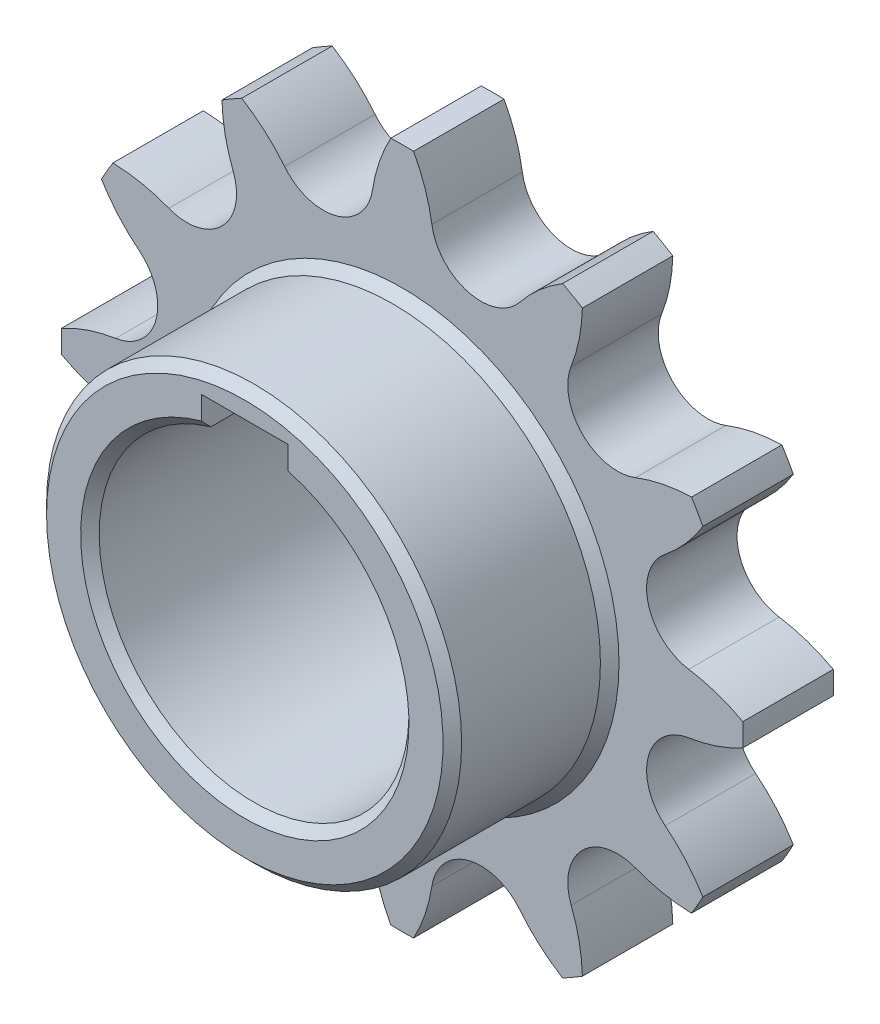
SolidWorks part; units mm, degrees
ref_plane "Front" through (0, 0, 0) normal (0, 0, 1) x (1, 0, 0)
ref_plane "Top" through (0, 0, 0) normal (0, 1, 0) x (1, 0, 0)
ref_plane "Right" through (0, 0, 0) normal (1, 0, 0) x (0, 0, -1)
sketch "Sketch1" plane through (0, 0, 0) normal (0, 0, 1) x (1, 0, 0)
  line L4 (0, -58.017) -> (0, 58.017) construction
  line L5 (-58.017, 0) -> (58.017, 0) construction
  line L6 (-1.75, -1.75) -> (1.75, 1.75)
  line L7 (-1.75, 1.75) -> (1.75, -1.75)
  circle A64 centre (0, 0) radius 41.129 construction
  circle A65 centre (0, 0) radius 49.069 construction
  arc A66 (42.4542, 18.9748) -> (46.2538, 4.7945) centre (47.4737, 12.7206) ccw
  arc A67 (54.9863, 1.8387) -> (46.2538, 4.7945) centre (42.1954, -21.5734) ccw
  arc A68 (48.5389, 25.9008) -> (46.7002, 29.0856) centre (0, 0) ccw
  arc A69 (42.4542, 18.9748) -> (48.5389, 25.9008) centre (25.7556, 39.7808) ccw
  arc A70 (27.279, 37.6597) -> (37.6597, 27.279) centre (34.7532, 34.7532) ccw
  arc A71 (46.7002, 29.0856) -> (37.6597, 27.279) centre (47.329, 2.4146) ccw
  arc A72 (29.0856, 46.7002) -> (25.9008, 48.5389) centre (0, 0) ccw
  arc A73 (27.279, 37.6597) -> (29.0856, 46.7002) centre (2.4146, 47.329) ccw
  arc A74 (4.7945, 46.2538) -> (18.9748, 42.4542) centre (12.7206, 47.4737) ccw
  arc A75 (25.9008, 48.5389) -> (18.9748, 42.4542) centre (39.7808, 25.7556) ccw
  arc A76 (1.8387, 54.9863) -> (-1.8387, 54.9863) centre (0, 0) ccw
  arc A77 (4.7945, 46.2538) -> (1.8387, 54.9863) centre (-21.5734, 42.1954) ccw
  arc A78 (-18.9748, 42.4542) -> (-4.7945, 46.2538) centre (-12.7206, 47.4737) ccw
  arc A79 (-1.8387, 54.9863) -> (-4.7945, 46.2538) centre (21.5734, 42.1954) ccw
  arc A80 (-25.9008, 48.5389) -> (-29.0856, 46.7002) centre (0, 0) ccw
  arc A81 (-18.9748, 42.4542) -> (-25.9008, 48.5389) centre (-39.7808, 25.7556) ccw
  arc A82 (-37.6597, 27.279) -> (-27.279, 37.6597) centre (-34.7532, 34.7532) ccw
  arc A83 (-29.0856, 46.7002) -> (-27.279, 37.6597) centre (-2.4146, 47.329) ccw
  arc A84 (-46.7002, 29.0856) -> (-48.5389, 25.9008) centre (0, 0) ccw
  arc A85 (-37.6597, 27.279) -> (-46.7002, 29.0856) centre (-47.329, 2.4146) ccw
  arc A86 (-46.2538, 4.7945) -> (-42.4542, 18.9748) centre (-47.4737, 12.7206) ccw
  arc A87 (-48.5389, 25.9008) -> (-42.4542, 18.9748) centre (-25.7556, 39.7808) ccw
  arc A88 (-54.9863, 1.8387) -> (-54.9863, -1.8387) centre (0, 0) ccw
  arc A89 (-46.2538, 4.7945) -> (-54.9863, 1.8387) centre (-42.1954, -21.5734) ccw
  arc A90 (-42.4542, -18.9748) -> (-46.2538, -4.7945) centre (-47.4737, -12.7206) ccw
  arc A91 (-54.9863, -1.8387) -> (-46.2538, -4.7945) centre (-42.1954, 21.5734) ccw
  arc A92 (-48.5389, -25.9008) -> (-46.7002, -29.0856) centre (0, 0) ccw
  arc A93 (-42.4542, -18.9748) -> (-48.5389, -25.9008) centre (-25.7556, -39.7808) ccw
  arc A94 (-27.279, -37.6597) -> (-37.6597, -27.279) centre (-34.7532, -34.7532) ccw
  arc A95 (-46.7002, -29.0856) -> (-37.6597, -27.279) centre (-47.329, -2.4146) ccw
  arc A96 (-29.0856, -46.7002) -> (-25.9008, -48.5389) centre (0, 0) ccw
  arc A97 (-27.279, -37.6597) -> (-29.0856, -46.7002) centre (-2.4146, -47.329) ccw
  arc A98 (-4.7945, -46.2538) -> (-18.9748, -42.4542) centre (-12.7206, -47.4737) ccw
  arc A99 (-25.9008, -48.5389) -> (-18.9748, -42.4542) centre (-39.7808, -25.7556) ccw
  arc A100 (-1.8387, -54.9863) -> (1.8387, -54.9863) centre (0, 0) ccw
  arc A101 (-4.7945, -46.2538) -> (-1.8387, -54.9863) centre (21.5734, -42.1954) ccw
  arc A102 (18.9748, -42.4542) -> (4.7945, -46.2538) centre (12.7206, -47.4737) ccw
  arc A103 (1.8387, -54.9863) -> (4.7945, -46.2538) centre (-21.5734, -42.1954) ccw
  arc A104 (25.9008, -48.5389) -> (29.0856, -46.7002) centre (0, 0) ccw
  arc A105 (18.9748, -42.4542) -> (25.9008, -48.5389) centre (39.7808, -25.7556) ccw
  arc A106 (37.6597, -27.279) -> (27.279, -37.6597) centre (34.7532, -34.7532) ccw
  arc A107 (29.0856, -46.7002) -> (27.279, -37.6597) centre (2.4146, -47.329) ccw
  arc A108 (46.7002, -29.0856) -> (48.5389, -25.9008) centre (0, 0) ccw
  arc A109 (37.6597, -27.279) -> (46.7002, -29.0856) centre (47.329, -2.4146) ccw
  arc A110 (46.2538, -4.7945) -> (42.4542, -18.9748) centre (47.4737, -12.7206) ccw
  arc A111 (48.5389, -25.9008) -> (42.4542, -18.9748) centre (25.7556, -39.7808) ccw
  arc A112 (54.9863, -1.8387) -> (54.9863, 1.8387) centre (0, 0) ccw
  arc A113 (46.2538, -4.7945) -> (54.9863, -1.8387) centre (42.1954, 21.5734) ccw
  circle A114 centre (0, 0) radius 25
  circle A115 centre (0, 0) radius 1.75
sketch "Sketch2" plane through (0, 0, 0) normal (0, 0, 1) x (1, 0, 0)
  circle A0 centre (0, 0) radius 25 construction
  arc A123 (-18.9748, 42.4542) -> (-25.9008, 48.5389) centre (-39.7808, 25.7556) ccw construction
  arc A124 (-25.9008, 48.5389) -> (-29.0856, 46.7002) centre (0, 0) ccw construction
  arc A125 (-29.0856, 46.7002) -> (-27.279, 37.6597) centre (-2.4146, 47.329) ccw construction
  arc A126 (-37.6597, 27.279) -> (-27.279, 37.6597) centre (-34.7532, 34.7532) ccw construction
  arc A127 (-37.6597, 27.279) -> (-46.7002, 29.0856) centre (-47.329, 2.4146) ccw construction
  arc A128 (-46.7002, 29.0856) -> (-48.5389, 25.9008) centre (0, 0) ccw construction
  arc A129 (-48.5389, 25.9008) -> (-42.4542, 18.9748) centre (-25.7556, 39.7808) ccw construction
  arc A130 (-46.2538, 4.7945) -> (-42.4542, 18.9748) centre (-47.4737, 12.7206) ccw construction
  arc A131 (-46.2538, 4.7945) -> (-54.9863, 1.8387) centre (-42.1954, -21.5734) ccw construction
  arc A132 (-54.9863, 1.8387) -> (-54.9863, -1.8387) centre (0, 0) ccw construction
  arc A133 (-54.9863, -1.8387) -> (-46.2538, -4.7945) centre (-42.1954, 21.5734) ccw construction
  arc A134 (-42.4542, -18.9748) -> (-46.2538, -4.7945) centre (-47.4737, -12.7206) ccw construction
  arc A135 (-42.4542, -18.9748) -> (-48.5389, -25.9008) centre (-25.7556, -39.7808) ccw construction
  arc A136 (-48.5389, -25.9008) -> (-46.7002, -29.0856) centre (0, 0) ccw construction
  arc A137 (-46.7002, -29.0856) -> (-37.6597, -27.279) centre (-47.329, -2.4146) ccw construction
  arc A138 (-27.279, -37.6597) -> (-37.6597, -27.279) centre (-34.7532, -34.7532) ccw construction
  arc A139 (-27.279, -37.6597) -> (-29.0856, -46.7002) centre (-2.4146, -47.329) ccw construction
  arc A140 (-29.0856, -46.7002) -> (-25.9008, -48.5389) centre (0, 0) ccw construction
  arc A141 (-25.9008, -48.5389) -> (-18.9748, -42.4542) centre (-39.7808, -25.7556) ccw construction
  arc A142 (-4.7945, -46.2538) -> (-18.9748, -42.4542) centre (-12.7206, -47.4737) ccw construction
  arc A143 (-4.7945, -46.2538) -> (-1.8387, -54.9863) centre (21.5734, -42.1954) ccw construction
  arc A144 (-1.8387, -54.9863) -> (1.8387, -54.9863) centre (0, 0) ccw construction
  arc A145 (1.8387, -54.9863) -> (4.7945, -46.2538) centre (-21.5734, -42.1954) ccw construction
  arc A146 (18.9748, -42.4542) -> (4.7945, -46.2538) centre (12.7206, -47.4737) ccw construction
  arc A147 (18.9748, -42.4542) -> (25.9008, -48.5389) centre (39.7808, -25.7556) ccw construction
  arc A148 (25.9008, -48.5389) -> (29.0856, -46.7002) centre (0, 0) ccw construction
  arc A149 (29.0856, -46.7002) -> (27.279, -37.6597) centre (2.4146, -47.329) ccw construction
  arc A150 (37.6597, -27.279) -> (27.279, -37.6597) centre (34.7532, -34.7532) ccw construction
  arc A151 (37.6597, -27.279) -> (46.7002, -29.0856) centre (47.329, -2.4146) ccw construction
  arc A152 (46.7002, -29.0856) -> (48.5389, -25.9008) centre (0, 0) ccw construction
  arc A153 (48.5389, -25.9008) -> (42.4542, -18.9748) centre (25.7556, -39.7808) ccw construction
  arc A154 (46.2538, -4.7945) -> (42.4542, -18.9748) centre (47.4737, -12.7206) ccw construction
  arc A155 (46.2538, -4.7945) -> (54.9863, -1.8387) centre (42.1954, 21.5734) ccw construction
  arc A156 (54.9863, -1.8387) -> (54.9863, 1.8387) centre (0, 0) ccw construction
  arc A157 (54.9863, 1.8387) -> (46.2538, 4.7945) centre (42.1954, -21.5734) ccw construction
  arc A158 (42.4542, 18.9748) -> (46.2538, 4.7945) centre (47.4737, 12.7206) ccw construction
  arc A159 (42.4542, 18.9748) -> (48.5389, 25.9008) centre (25.7556, 39.7808) ccw construction
  arc A160 (48.5389, 25.9008) -> (46.7002, 29.0856) centre (0, 0) ccw construction
  arc A161 (46.7002, 29.0856) -> (37.6597, 27.279) centre (47.329, 2.4146) ccw construction
  arc A162 (27.279, 37.6597) -> (37.6597, 27.279) centre (34.7532, 34.7532) ccw construction
  arc A163 (27.279, 37.6597) -> (29.0856, 46.7002) centre (2.4146, 47.329) ccw construction
  arc A164 (29.0856, 46.7002) -> (25.9008, 48.5389) centre (0, 0) ccw construction
  arc A165 (25.9008, 48.5389) -> (18.9748, 42.4542) centre (39.7808, 25.7556) ccw construction
  arc A166 (4.7945, 46.2538) -> (18.9748, 42.4542) centre (12.7206, 47.4737) ccw construction
  arc A167 (4.7945, 46.2538) -> (1.8387, 54.9863) centre (-21.5734, 42.1954) ccw construction
  arc A168 (1.8387, 54.9863) -> (-1.8387, 54.9863) centre (0, 0) ccw construction
  arc A169 (-1.8387, 54.9863) -> (-4.7945, 46.2538) centre (21.5734, 42.1954) ccw construction
  arc A170 (-18.9748, 42.4542) -> (-4.7945, 46.2538) centre (-12.7206, 47.4737) ccw construction
  circle A171 centre (0, 0) radius 25
  arc A172 (-18.9748, 42.4542) -> (-25.9008, 48.5389) centre (-39.7808, 25.7556) ccw
  arc A173 (-25.9008, 48.5389) -> (-29.0856, 46.7002) centre (0, 0) ccw
  arc A174 (-29.0856, 46.7002) -> (-27.279, 37.6597) centre (-2.4146, 47.329) ccw
  arc A175 (-37.6597, 27.279) -> (-27.279, 37.6597) centre (-34.7532, 34.7532) ccw
  arc A176 (-37.6597, 27.279) -> (-46.7002, 29.0856) centre (-47.329, 2.4146) ccw
  arc A177 (-46.7002, 29.0856) -> (-48.5389, 25.9008) centre (0, 0) ccw
  arc A178 (-48.5389, 25.9008) -> (-42.4542, 18.9748) centre (-25.7556, 39.7808) ccw
  arc A179 (-46.2538, 4.7945) -> (-42.4542, 18.9748) centre (-47.4737, 12.7206) ccw
  arc A180 (-46.2538, 4.7945) -> (-54.9863, 1.8387) centre (-42.1954, -21.5734) ccw
  arc A181 (-54.9863, 1.8387) -> (-54.9863, -1.8387) centre (0, 0) ccw
  arc A182 (-54.9863, -1.8387) -> (-46.2538, -4.7945) centre (-42.1954, 21.5734) ccw
  arc A183 (-42.4542, -18.9748) -> (-46.2538, -4.7945) centre (-47.4737, -12.7206) ccw
  arc A184 (-42.4542, -18.9748) -> (-48.5389, -25.9008) centre (-25.7556, -39.7808) ccw
  arc A185 (-48.5389, -25.9008) -> (-46.7002, -29.0856) centre (0, 0) ccw
  arc A186 (-46.7002, -29.0856) -> (-37.6597, -27.279) centre (-47.329, -2.4146) ccw
  arc A187 (-27.279, -37.6597) -> (-37.6597, -27.279) centre (-34.7532, -34.7532) ccw
  arc A188 (-27.279, -37.6597) -> (-29.0856, -46.7002) centre (-2.4146, -47.329) ccw
  arc A189 (-29.0856, -46.7002) -> (-25.9008, -48.5389) centre (0, 0) ccw
  arc A190 (-25.9008, -48.5389) -> (-18.9748, -42.4542) centre (-39.7808, -25.7556) ccw
  arc A191 (-4.7945, -46.2538) -> (-18.9748, -42.4542) centre (-12.7206, -47.4737) ccw
  arc A192 (-4.7945, -46.2538) -> (-1.8387, -54.9863) centre (21.5734, -42.1954) ccw
  arc A193 (-1.8387, -54.9863) -> (1.8387, -54.9863) centre (0, 0) ccw
  arc A194 (1.8387, -54.9863) -> (4.7945, -46.2538) centre (-21.5734, -42.1954) ccw
  arc A195 (18.9748, -42.4542) -> (4.7945, -46.2538) centre (12.7206, -47.4737) ccw
  arc A196 (18.9748, -42.4542) -> (25.9008, -48.5389) centre (39.7808, -25.7556) ccw
  arc A197 (25.9008, -48.5389) -> (29.0856, -46.7002) centre (0, 0) ccw
  arc A198 (29.0856, -46.7002) -> (27.279, -37.6597) centre (2.4146, -47.329) ccw
  arc A199 (37.6597, -27.279) -> (27.279, -37.6597) centre (34.7532, -34.7532) ccw
  arc A200 (37.6597, -27.279) -> (46.7002, -29.0856) centre (47.329, -2.4146) ccw
  arc A201 (46.7002, -29.0856) -> (48.5389, -25.9008) centre (0, 0) ccw
  arc A202 (48.5389, -25.9008) -> (42.4542, -18.9748) centre (25.7556, -39.7808) ccw
  arc A203 (46.2538, -4.7945) -> (42.4542, -18.9748) centre (47.4737, -12.7206) ccw
  arc A204 (46.2538, -4.7945) -> (54.9863, -1.8387) centre (42.1954, 21.5734) ccw
  arc A205 (54.9863, -1.8387) -> (54.9863, 1.8387) centre (0, 0) ccw
  arc A206 (54.9863, 1.8387) -> (46.2538, 4.7945) centre (42.1954, -21.5734) ccw
  arc A207 (42.4542, 18.9748) -> (46.2538, 4.7945) centre (47.4737, 12.7206) ccw
  arc A208 (42.4542, 18.9748) -> (48.5389, 25.9008) centre (25.7556, 39.7808) ccw
  arc A209 (48.5389, 25.9008) -> (46.7002, 29.0856) centre (0, 0) ccw
  arc A210 (46.7002, 29.0856) -> (37.6597, 27.279) centre (47.329, 2.4146) ccw
  arc A211 (27.279, 37.6597) -> (37.6597, 27.279) centre (34.7532, 34.7532) ccw
  arc A212 (27.279, 37.6597) -> (29.0856, 46.7002) centre (2.4146, 47.329) ccw
  arc A213 (29.0856, 46.7002) -> (25.9008, 48.5389) centre (0, 0) ccw
  arc A214 (25.9008, 48.5389) -> (18.9748, 42.4542) centre (39.7808, 25.7556) ccw
  arc A215 (4.7945, 46.2538) -> (18.9748, 42.4542) centre (12.7206, 47.4737) ccw
  arc A216 (4.7945, 46.2538) -> (1.8387, 54.9863) centre (-21.5734, 42.1954) ccw
  arc A217 (1.8387, 54.9863) -> (-1.8387, 54.9863) centre (0, 0) ccw
  arc A218 (-1.8387, 54.9863) -> (-4.7945, 46.2538) centre (21.5734, 42.1954) ccw
  arc A219 (-18.9748, 42.4542) -> (-4.7945, 46.2538) centre (-12.7206, 47.4737) ccw
extrude "Boss-Extrude1" add sketch "Sketch2" along normal blind 14.6
sketch "Sketch3" plane through (0, 0, 0) normal (0, 0, -1) x (-1, 0, 0)
  circle A0 centre (0, 0) radius 33.5
  circle A1 centre (0, 0) radius 25
  dimension "D1" = 50
  dimension "D2" = 67
extrude "Boss-Extrude2" add sketch "Sketch3" against normal blind 40
sketch "Sketch6" plane through (0, 0, 40) normal (0, 0, 1) x (1, 0, 0)
  line L0 (0, 0) -> (0, 29) construction
  line L6 (-7, 29.3) -> (7, 29.3)
  line L7 (-7, 29.3) -> (-7, 17.3)
  line L8 (-7, 17.3) -> (7, 17.3)
  line L9 (7, 29.3) -> (7, 17.3)
  dimension "D1" = 29
  dimension "D2" = 14
  dimension "D3" = 12
  dimension "D4" = 0.3
extrude "Cut-Extrude1" cut sketch "Sketch6" against normal blind 64 contours L8 L9 L6 L7
chamfer "Chamfer1" distance 1.5 angle 45 3 edges at (0, -25, 40) (-33.5, 0, 40) (33.5, 0, 14.6)
